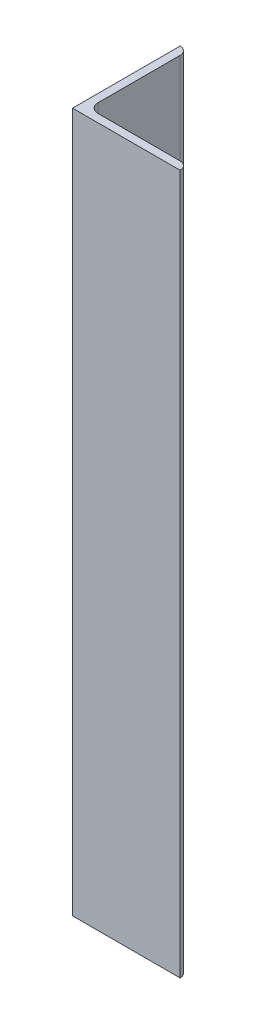
SolidWorks part; units mm, degrees
ref_plane "Front Plane" through (0, 0, 0) normal (0, 0, 1) x (1, 0, 0)
ref_plane "Top Plane" through (0, 0, 0) normal (0, 1, 0) x (1, 0, 0)
ref_plane "Right Plane" through (0, 0, 0) normal (1, 0, 0) x (0, 0, -1)
sketch3d "3DSketch1"
  line L0 (0, 0, 0) -> (0, 260, 0)
  dimension "D1" = 260
other "Iron V40X40X3(1)"
ref_plane "Plane1" through (0, 0, 0) normal (0, 1, 0) x (1, 0, 0)
sketch "Sketch1" plane through (0, 0, 0) normal (0, 1, 0) x (1, 0, 0)
  line L0 (0, 0) -> (0, 40)
  line L1 (0, 20) -> (3, 20) construction
  line L2 (3, 37) -> (3, 6.5)
  line L3 (6.5, 3) -> (37, 3)
  line L4 (20, 3) -> (20, 0) construction
  line L5 (40, 0) -> (0, 0)
  arc A0 (40, 0) -> (37, 3) centre (37, 0) ccw
  arc A1 (0, 40) -> (3, 37) centre (0, 37) cw
  arc A2 (6.5, 3) -> (3, 6.5) centre (6.5, 6.5) cw
  point P10 (20, 0)
  point P14 (0, 20)
  point P15 (3, 20)
  point P16 (20, 3)
  point P17 (3, 40)
  point P18 (40, 3)
  point P21 (0, 0)
  dimension "D2" = 3
  dimension "D3" = 40
  dimension "Radius_1" = 3.5
  dimension "D1" = 3
